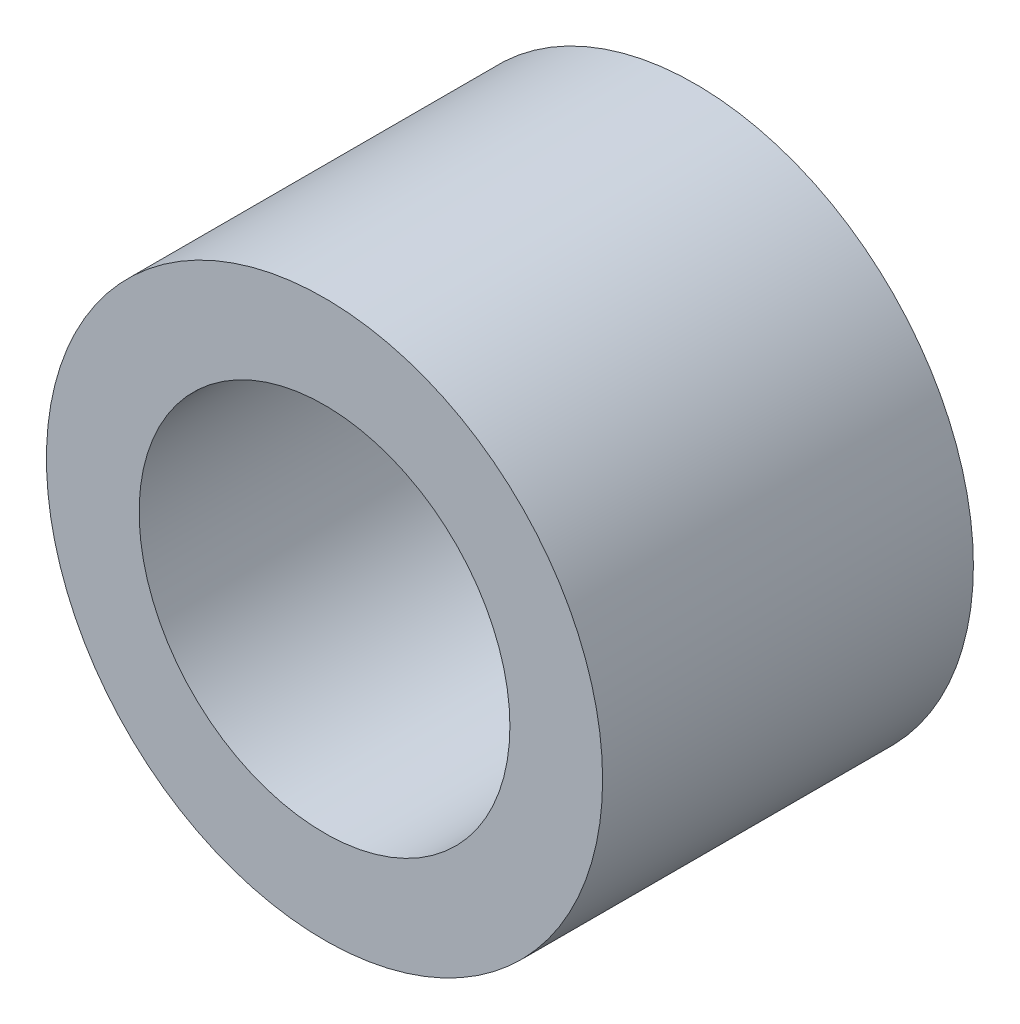
SolidWorks part; units mm, degrees
material "黄銅"
ref_plane "正面" through (0, 0, 0) normal (0, 0, 1) x (1, 0, 0)
ref_plane "平面" through (0, 0, 0) normal (0, 1, 0) x (1, 0, 0)
ref_plane "右側面" through (0, 0, 0) normal (1, 0, 0) x (0, 0, -1)
sketch "ｽｹｯﾁ1" plane through (0, 0, 0) normal (0, 0, 1) x (1, 0, 0)
  circle A0 centre (0, 0) radius 3
  dimension "D1" = 6
extrude "ﾎﾞｽ - 押し出し1" add sketch "ｽｹｯﾁ1" along normal blind 4
sketch "ｽｹｯﾁ2" plane through (0, 0, 4) normal (0, 0, 1) x (1, 0, 0)
  circle A0 centre (0, 0) radius 2
  dimension "D1" = 4
extrude "ｶｯﾄ - 押し出し1" cut sketch "ｽｹｯﾁ2" against normal through all
